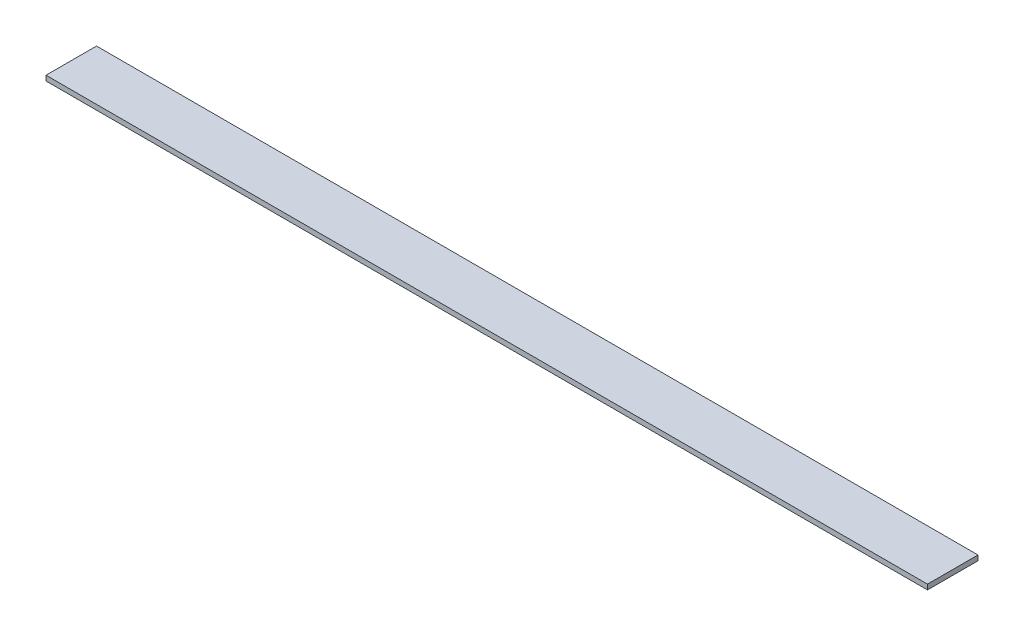
SolidWorks part; units mm, degrees
ref_plane "Front Plane" through (0, 0, 0) normal (0, 0, 1) x (1, 0, 0)
ref_plane "Top Plane" through (0, 0, 0) normal (0, 1, 0) x (1, 0, 0)
ref_plane "Right Plane" through (0, 0, 0) normal (1, 0, 0) x (0, 0, -1)
sketch "Sketch1" plane through (0, 0, 0) normal (1, 0, 0) x (0, 0, -1)
  line L0 (0, 0) -> (25.4, 0)
  line L1 (0, 0) -> (0, 2.54)
  line L2 (25.4, 0) -> (25.4, 2.54)
  line L3 (0, 2.54) -> (25.4, 2.54)
  dimension "D1" = 2.54
  dimension "D2" = 25.4
extrude "Boss-Extrude1" add sketch "Sketch1" along normal blind 443.23
